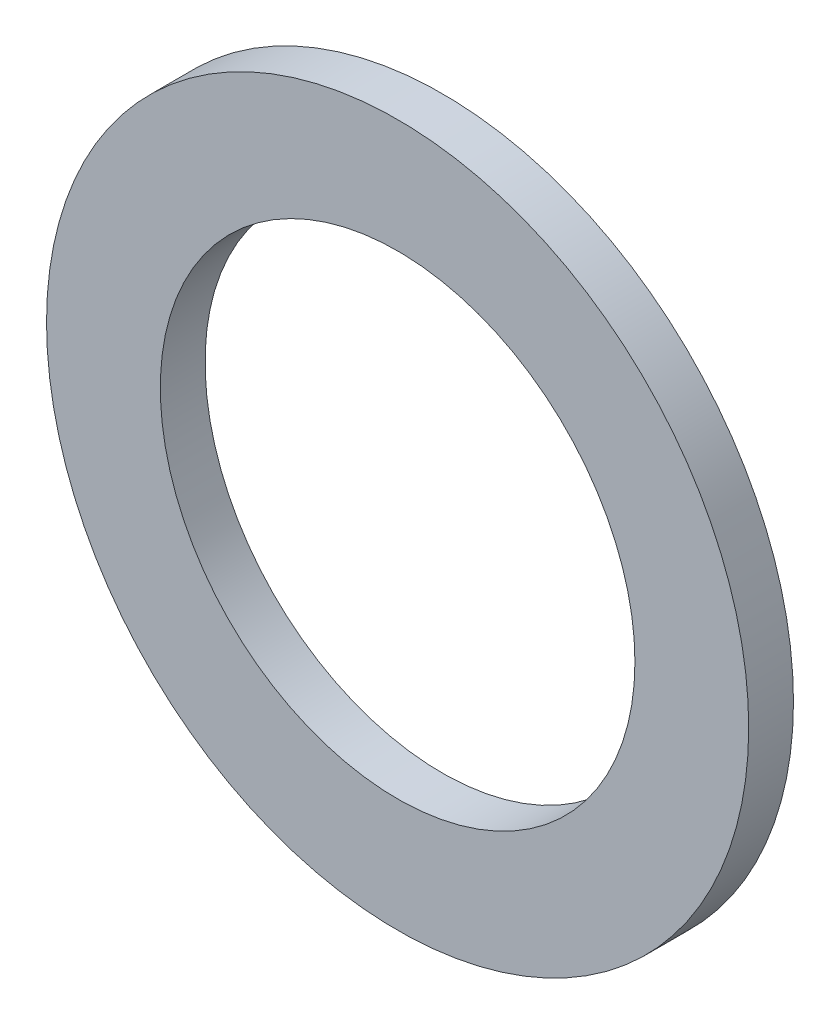
SolidWorks part; units mm, degrees
ref_plane "Front" through (0, 0, 0) normal (0, 0, 1) x (1, 0, 0)
ref_plane "Top" through (0, 0, 0) normal (0, 1, 0) x (1, 0, 0)
ref_plane "Right" through (0, 0, 0) normal (1, 0, 0) x (0, 0, -1)
sketch "Sketch1" plane through (0, 0, 0) normal (0, 0, 1) x (1, 0, 0)
  circle A0 centre (0, 0) radius 26.51
  circle A1 centre (0, 0) radius 39.22
  dimension "D1" = 78.44
  dimension "D2" = 53.02
extrude "Boss-Extrude1" add sketch "Sketch1" along normal blind 5
